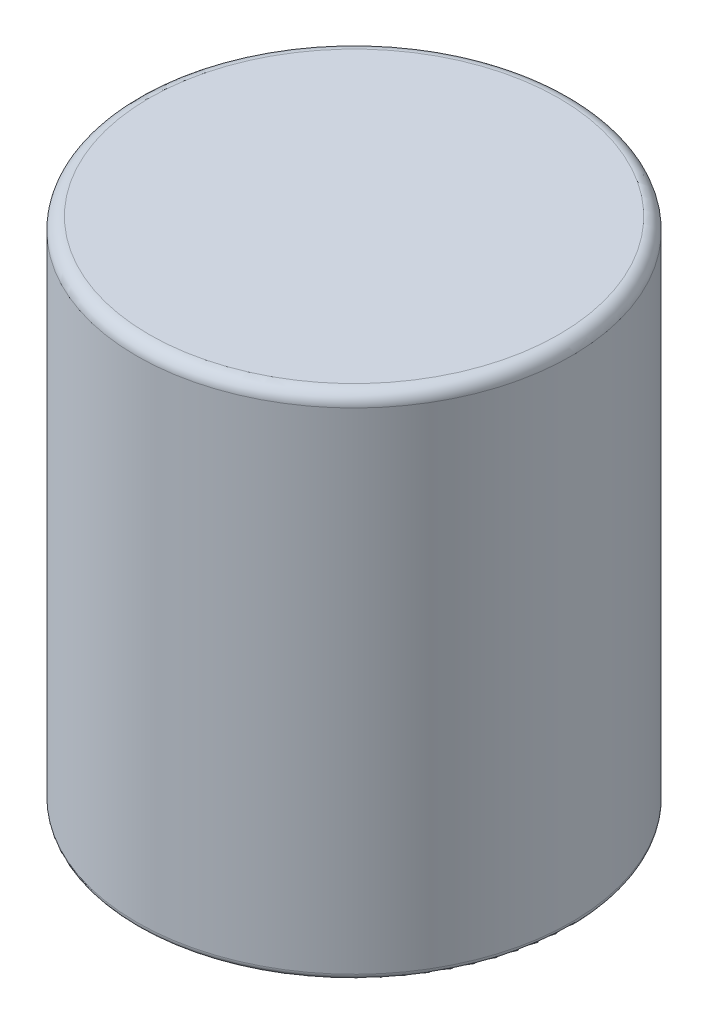
SolidWorks part; units mm, degrees
ref_plane "Front Plane" through (0, 0, 0) normal (0, 0, 1) x (1, 0, 0)
ref_plane "Top Plane" through (0, 0, 0) normal (0, 1, 0) x (1, 0, 0)
ref_plane "Right Plane" through (0, 0, 0) normal (1, 0, 0) x (0, 0, -1)
sketch "Sketch1" plane through (0, 0, 0) normal (0, 1, 0) x (1, 0, 0)
  circle A0 centre (0, 0) radius 17.5
  dimension "D1" = 35
extrude "Boss-Extrude1" add sketch "Sketch1" along normal blind 41
fillet "Fillet2" radius 1 1 edges at (0, 41, 17.5)
sketch "Sketch2" plane through (0, 0, 0) normal (0, -1, 0) x (1, 0, 0)
  circle A2 centre (0, 5) radius 0.6
  circle A3 centre (0, -5) radius 0.6
  dimension "D1" = 5
  dimension "D2" = 5
  dimension "D3" = 1.2
  dimension "D4" = 1.2
  dimension "D5" = 10
extrude "Boss-Extrude2" add sketch "Sketch2" along normal blind 5
fillet "Fillet3" radius 0.5 1 edges at (0, 0, 17.5)
